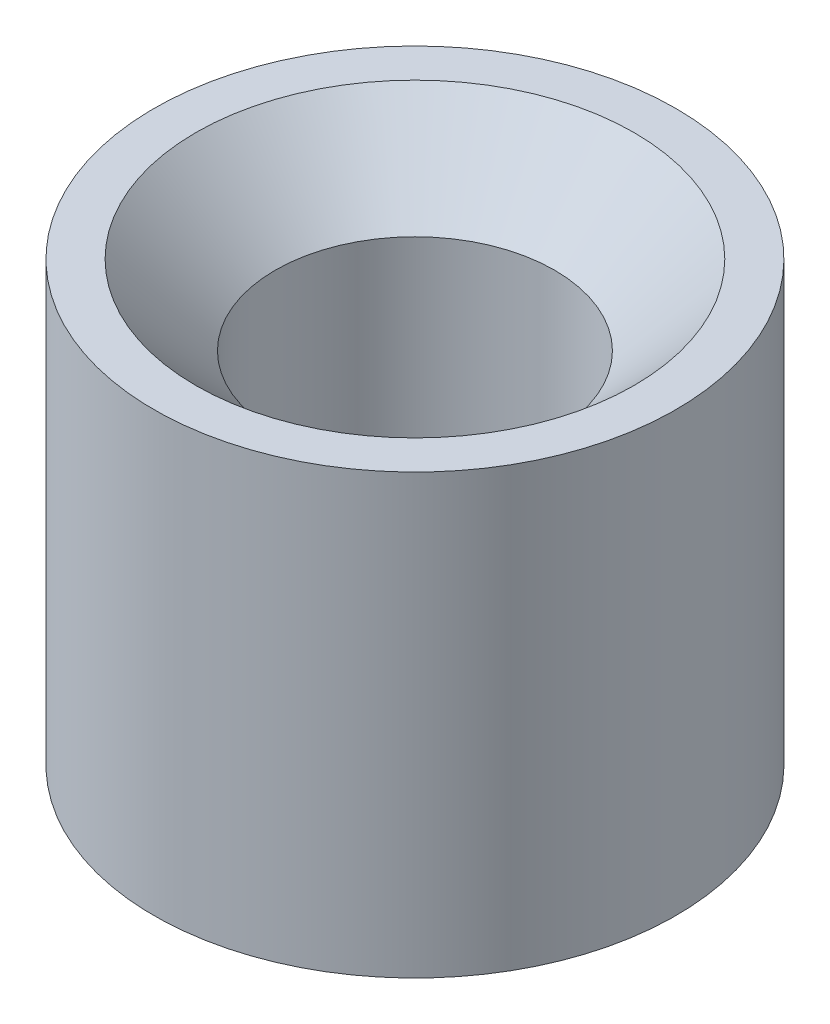
SolidWorks part; units mm, degrees
material "黄铜"
ref_plane "前视基准面" through (0, 0, 0) normal (0, 0, 1) x (1, 0, 0)
ref_plane "上视基准面" through (0, 0, 0) normal (0, 1, 0) x (1, 0, 0)
ref_plane "右视基准面" through (0, 0, 0) normal (1, 0, 0) x (0, 0, -1)
sketch "草图1" plane through (0, 0, 0) normal (0, 0, 1) x (1, 0, 0)
  line L0 (3.12, 0) -> (3.12, 5.24)
  line L1 (3.12, 5.24) -> (2.62, 5.24)
  line L2 (2.62, 5.24) -> (1.67, 4.29)
  line L3 (1.67, 4.29) -> (1.67, 0.95)
  line L4 (1.67, 0.95) -> (2.62, 0)
  line L5 (2.62, 0) -> (3.12, 0)
  line L6 (0, 0) -> (0, 7.3604) construction
  dimension "D1" = 5.24
  dimension "D2" = 3.12
  dimension "D3" = 1.67
  dimension "D4" = 2.62
  dimension "D5" = 45
  dimension "D6" = 45
revolve "旋转1" add sketch "草图1" angle 360 about L6
cosmetic thread "装饰螺纹线1" parameters "D1"=5, "D2"=5
